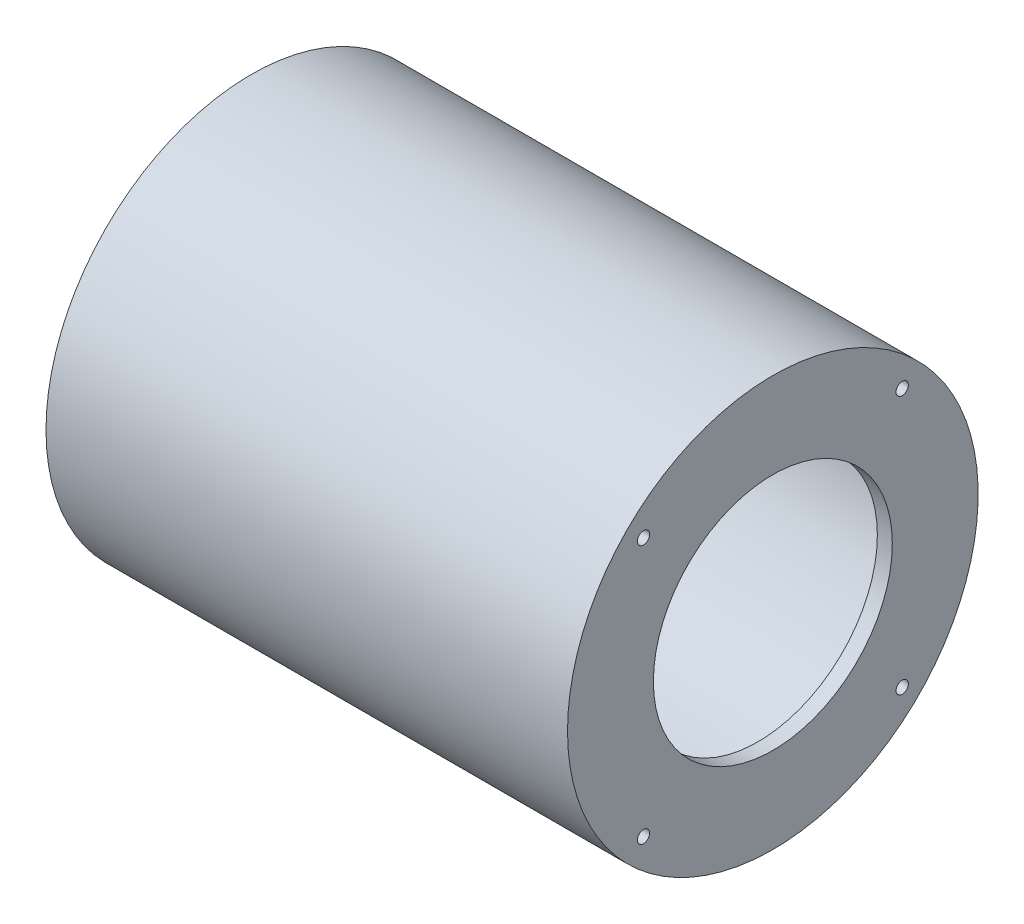
SolidWorks part; units mm, degrees
ref_plane "Front Plane" through (0, 0, 0) normal (0, 0, 1) x (1, 0, 0)
ref_plane "Top Plane" through (0, 0, 0) normal (0, 1, 0) x (1, 0, 0)
ref_plane "Right Plane" through (0, 0, 0) normal (1, 0, 0) x (0, 0, -1)
sketch "Axial profile (mm)" plane through (0, 0, 0) normal (0, 0, 1) x (1, 0, 0)
  line L0 (-110, 0) -> (75, 0) construction
  line L1 (-126, 52) -> (9.7, 52)
  line L2 (9.7, 52) -> (9.7, 32)
  line L3 (9.7, 32) -> (13.7, 32)
  line L4 (13.7, 32) -> (13.7, 55)
  line L5 (13.7, 55) -> (-126, 55)
  line L6 (-126, 55) -> (-126, 52)
revolve "Full revolution" add sketch "Axial profile (mm)" angle 360 about L0
sketch "Sketch2" plane through (0, 0, 0) normal (1, 0, 0) x (0, 0, -1)
  circle A0 centre (-34.6482, 34.6482) radius 1.65
  circle A1 centre (-34.6482, -34.6482) radius 1.65
  circle A2 centre (34.6482, -34.6482) radius 1.65
  circle A3 centre (34.6482, 34.6482) radius 1.65
extrude "Axial holes" cut sketch "Sketch2" along normal blind 4 from offset 9.7
